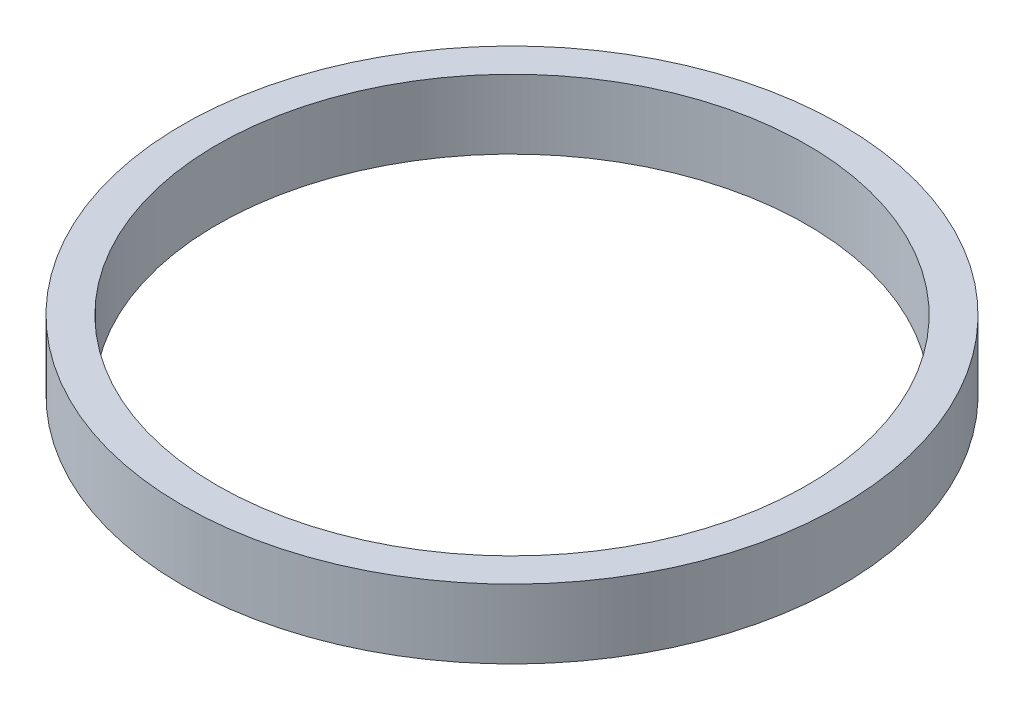
SolidWorks part; units mm, degrees
ref_plane "Front Plane" through (0, 0, 0) normal (0, 0, 1) x (1, 0, 0)
ref_plane "Top Plane" through (0, 0, 0) normal (0, 1, 0) x (1, 0, 0)
ref_plane "Right Plane" through (0, 0, 0) normal (1, 0, 0) x (0, 0, -1)
sketch "Sketch1" plane through (0, 0, 0) normal (0, 1, 0) x (1, 0, 0)
  circle A0 centre (0, 0) radius 42.65
  circle A1 centre (0, 0) radius 47.65
  dimension "D1" = 85.3
  dimension "D2" = 95.3
extrude "Boss-Extrude1" add sketch "Sketch1" along normal blind 10
